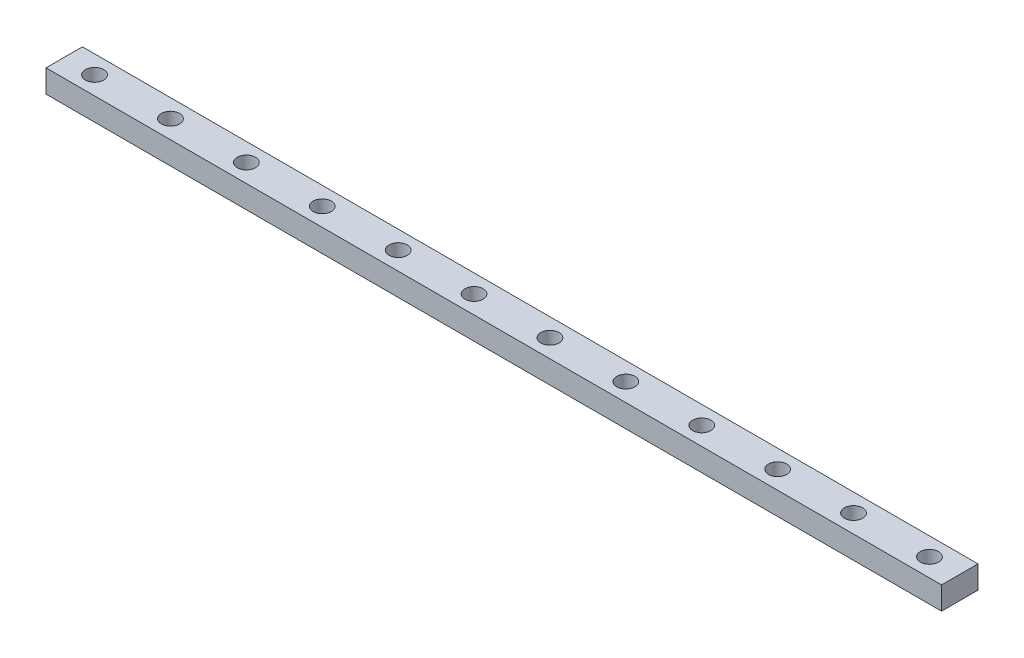
SolidWorks part; units mm, degrees
ref_plane "前视" through (0, 0, 0) normal (0, 0, 1) x (1, 0, 0)
ref_plane "上视" through (0, 0, 0) normal (0, 1, 0) x (1, 0, 0)
ref_plane "右视" through (0, 0, 0) normal (1, 0, 0) x (0, 0, -1)
sketch "草图2" plane through (0, 0, 0) normal (0, 1, 0) x (1, 0, 0)
  line L1 (0, 6) -> (295, 6)
  line L2 (0, 6) -> (0, -6)
  line L3 (0, -6) -> (295, -6)
  line L4 (295, 6) -> (295, -6)
  dimension "D1" = 12
  dimension "D2" = 6
  dimension "D3" = 295
extrude "拉伸1" add sketch "草图2" along normal blind 7.5
sketch "草图3" plane through (0, 7.5, 0) normal (0, 1, 0) x (1, 0, 0)
  point P0 (10, 0)
  dimension "D1" = 10
hole_wizard "M3 六角凹头螺钉的柱形沉头孔1" positions "3D草图1" profile "草图4" counterbore size "M3" standard "ISO" end condition through all
sketch3d "3D草图1"
  point P0 (10, 7.5, 0)
sketch "草图4" plane through (10, 7.5, 0) normal (1, 0, 0) x (0, 0, 1)
  line L0 (0, 0) -> (0, 7.5)
  line L1 (0, 7.5) -> (1.75, 7.5)
  line L3 (1.75, 7.5) -> (1.75, 4.5)
  line L4 (1.75, 4.5) -> (3, 4.5)
  line L5 (3, 4.5) -> (3, 0)
  line L7 (3, 0) -> (0, 0)
  line L11 (0, -6.35) -> (0, 107.95) construction
  dimension "通孔孔直径" = 3.5
  dimension "通孔孔深度" = 7.5
  dimension "柱形沉头孔直径" = 6
  dimension "柱形沉头孔深度" = 4.5
pattern_linear "阵列(线性)1" count 12 spacing 25 along (1, 0, 0) of "M3 六角凹头螺钉的柱形沉头孔1"
sketch "草图5" plane through (0, 0, 6) normal (0, 0, 1) x (1, 0, 0)
  line L0 (147.5, 0) -> (147.5, 7.5) construction
  line L1 (0, 0) -> (295, 0) construction
  line L2 (0, 7.5) -> (295, 7.5) construction
  point P6 (147.5, 3.75)
